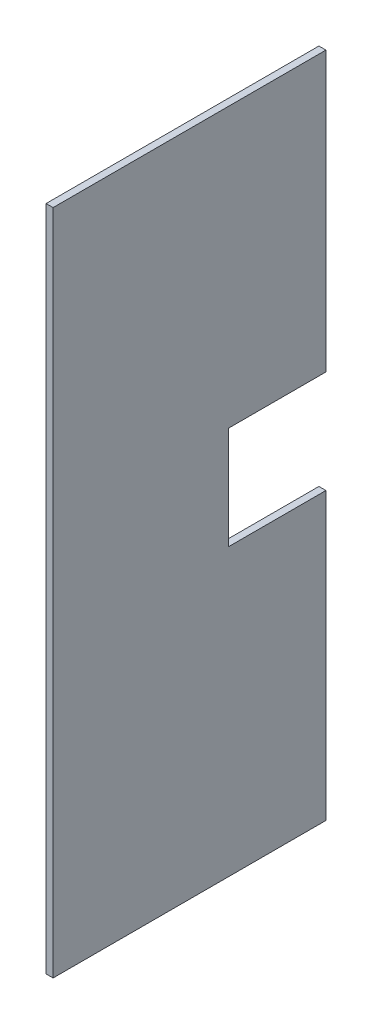
SolidWorks part; units mm, degrees
ref_plane "Спереди" through (0, 0, 0) normal (0, 0, 1) x (1, 0, 0)
ref_plane "Сверху" through (0, 0, 0) normal (0, 1, 0) x (1, 0, 0)
ref_plane "Справа" through (0, 0, 0) normal (1, 0, 0) x (0, 0, -1)
ref_plane "Плоскость4" through (0.5, 0, 0) normal (-1, 0, 0) x (0, -1, 0)
sketch "Эскиз1" plane through (0.5, 0, 0) normal (-1, 0, 0) x (0, -1, 0)
  line L0 (-5.85, 42.25) -> (-100.85, 42.25)
  line L1 (-100.85, 42.25) -> (-100.85, 3.4)
  line L2 (-100.85, 3.4) -> (-5.85, 3.4)
  line L3 (-5.85, 3.4) -> (-5.85, 42.25)
extrude "Бобышка-Вытянуть1" add sketch "Эскиз1" against normal blind 0.5
sketch "Эскиз2" plane through (0.5, 0, 0) normal (-1, 0, 0) x (0, 0, 1)
  line L0 (42.25, 5.85) -> (3.4, 5.85)
  line L1 (3.4, 5.85) -> (3.4, 100.85)
  line L2 (3.4, 100.85) -> (42.25, 100.85)
  line L3 (42.25, 100.85) -> (42.25, 5.85)
extrude "Бобышка-Вытянуть2" add sketch "Эскиз2" along normal blind 0.5
sketch "Эскиз3" plane through (0, 0, 0) normal (-1, 0, 0) x (0, 0, 1)
  line L0 (16.8066, 60.6559) -> (6.9066, 60.6559) construction
  line L1 (-5.3267, 46.5419) -> (17.3066, 46.5419)
  line L2 (-5.3267, 46.5419) -> (-5.3267, 61.1559)
  line L3 (-5.3267, 61.1559) -> (17.3066, 61.1559)
  line L4 (17.3066, 46.5419) -> (17.3066, 61.1559)
  line L5 (7.3592, 47.0419) -> (16.3539, 47.0419) construction
  line L6 (16.8066, 60.6559) -> (16.8066, 46.5359) construction
  dimension "D1" = 0.5
  dimension "D2" = 0.5
  dimension "D3" = 0.5
extrude "Вырез-Вытянуть1" cut sketch "Эскиз3" against normal through all
